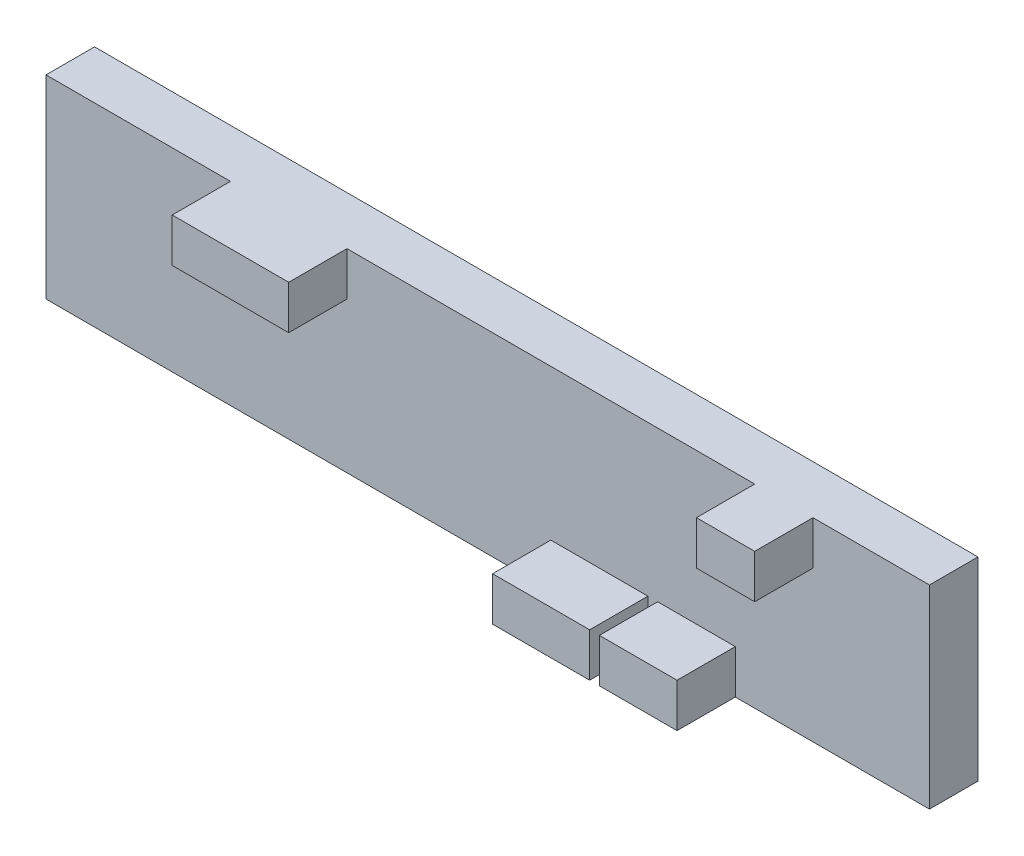
SolidWorks part; units mm, degrees
ref_plane "Спереди" through (0, 0, 0) normal (0, 0, 1) x (1, 0, 0)
ref_plane "Сверху" through (0, 0, 0) normal (0, 1, 0) x (1, 0, 0)
ref_plane "Справа" through (0, 0, 0) normal (1, 0, 0) x (0, 0, -1)
sketch "Эскиз1" plane through (0, 0, 0) normal (0, 0, 1) x (1, 0, 0)
  line L1 (0, 0) -> (91, 0)
  line L2 (0, 0) -> (0, 20)
  line L3 (0, 20) -> (91, 20)
  line L4 (91, 0) -> (91, 20)
extrude "Бобышка-Вытянуть1" add sketch "Эскиз1" along normal blind 5 contours L2 L1 L4 L3
sketch "Эскиз2" plane through (0, 0, 5) normal (0, 0, 1) x (1, 0, 0)
  line L0 (0, 20) -> (91, 20) construction
  line L1 (19, 20) -> (31, 20)
  line L2 (19, 20) -> (19, 15.5)
  line L3 (19, 15.5) -> (31, 15.5)
  line L4 (31, 20) -> (31, 15.5)
  line L5 (0, 0) -> (0, 20) construction
  line L6 (91, 0) -> (91, 20) construction
  line L7 (73, 20) -> (79, 20)
  line L8 (73, 20) -> (73, 15.5)
  line L9 (73, 15.5) -> (79, 15.5)
  line L10 (79, 20) -> (79, 15.5)
  line L20 (0, 0) -> (91, 0) construction
  line L21 (52, 0) -> (62, 0)
  line L22 (52, 0) -> (52, 4.5)
  line L23 (52, 4.5) -> (62, 4.5)
  line L24 (62, 0) -> (62, 4.5)
  line L26 (63, 0) -> (71, 0)
  line L27 (63, 0) -> (63, 4.5)
  line L28 (63, 4.5) -> (71, 4.5)
  line L29 (71, 0) -> (71, 4.5)
  point P24 (0, 0)
  point P25 (0, 0)
  point P26 (0, 0)
  dimension "D1" = 19
  dimension "D2" = 12
  dimension "D3" = 20
  dimension "D4" = 1
  dimension "D5" = 8
extrude "Бобышка-Вытянуть2" add sketch "Эскиз2" along normal blind 6
